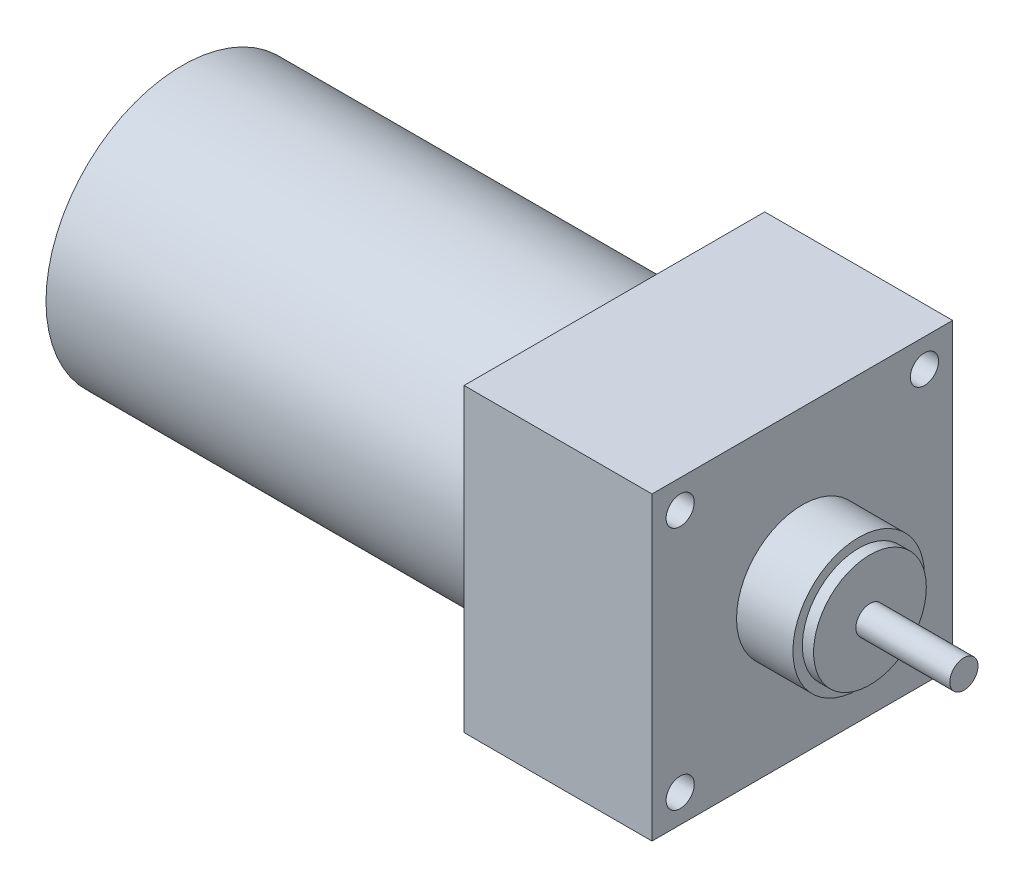
SolidWorks part; units mm, degrees
ref_plane "Front Plane" through (0, 0, 0) normal (0, 0, 1) x (1, 0, 0)
ref_plane "Top Plane" through (0, 0, 0) normal (0, 1, 0) x (1, 0, 0)
ref_plane "Right Plane" through (0, 0, 0) normal (1, 0, 0) x (0, 0, -1)
sketch "Sketch1" plane through (0, 0, 0) normal (1, 0, 0) x (0, 0, -1)
  line L1 (16, 16) -> (-16, 16)
  line L2 (16, 16) -> (16, -16)
  line L3 (16, -16) -> (-16, -16)
  line L4 (-16, 16) -> (-16, -16)
  line L5 (16, 16) -> (-16, -16) construction
  line L6 (16, -16) -> (-16, 16) construction
  point P0 (0, 0)
extrude "Boss-Extrude2" add sketch "Sketch1" along normal blind 20
sketch "Sketch2" plane through (0, 0, 0) normal (-1, 0, 0) x (0, 0, 1)
  circle A0 centre (0, 0) radius 14.5
extrude "Boss-Extrude3" add sketch "Sketch2" along normal blind 46
sketch "Sketch3" plane through (20, 0, 0) normal (1, 0, 0) x (0, 0, -1)
  circle A0 centre (0, 0) radius 7
extrude "Boss-Extrude4" add sketch "Sketch3" along normal blind 6
sketch "Sketch6" plane through (26, 0, 0) normal (1, 0, 0) x (0, 0, -1)
  circle A0 centre (0, 0) radius 6
extrude "Boss-Extrude5" add sketch "Sketch6" along normal blind 1.2
sketch "Sketch7" plane through (27.2, 0, 0) normal (1, 0, 0) x (0, 0, -1)
  circle A0 centre (0, 0) radius 1.5
extrude "Boss-Extrude6" add sketch "Sketch7" along normal blind 10
sketch "Sketch8" plane through (20, 0, 0) normal (1, 0, 0) x (0, 0, -1)
  line L1 (16, -16) -> (13, -16)
  line L2 (16, -16) -> (16, -13)
  line L3 (16, -13) -> (13, -13)
  line L4 (13, -16) -> (13, -13)
  line L5 (16, 16) -> (13, 16)
  line L6 (16, 16) -> (16, 13)
  line L7 (16, 13) -> (13, 13)
  line L8 (13, 16) -> (13, 13)
  line L9 (-16, 16) -> (-13, 16)
  line L10 (-16, 16) -> (-16, 13)
  line L11 (-16, 13) -> (-13, 13)
  line L12 (-13, 16) -> (-13, 13)
  line L13 (-16, -16) -> (-13, -16)
  line L14 (-16, -16) -> (-16, -13)
  line L15 (-16, -13) -> (-13, -13)
  line L16 (-13, -16) -> (-13, -13)
  circle A0 centre (13, -13) radius 1.5
  circle A1 centre (13, 13) radius 1.5
  circle A2 centre (-13, 13) radius 1.5
  circle A3 centre (-13, -13) radius 1.5
extrude "Cut-Extrude5" cut sketch "Sketch8" against normal blind 20 contours L16 A3 L15 | L15 A3 L16 | L4 A0 L3 | L3 A0 L4 | L8 A1 L7 | L7 A1 L8 | L12 A2 L11 | L11 A2 L12
